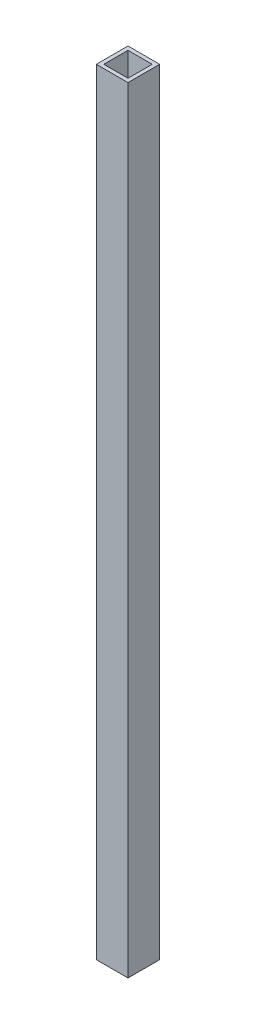
SolidWorks part; units mm, degrees
ref_plane "Front Plane" through (0, 0, 0) normal (0, 0, 1) x (1, 0, 0)
ref_plane "Top Plane" through (0, 0, 0) normal (0, 1, 0) x (1, 0, 0)
ref_plane "Right Plane" through (0, 0, 0) normal (1, 0, 0) x (0, 0, -1)
sketch "Sketch1" plane through (0, 0, 0) normal (0, 1, 0) x (1, 0, 0)
  line L1 (15.8767, 21.8352) -> (24.3767, 21.8352)
  line L2 (15.8767, 21.8352) -> (15.8767, 30.3352)
  line L3 (15.8767, 30.3352) -> (24.3767, 30.3352)
  line L4 (24.3767, 21.8352) -> (24.3767, 30.3352)
  line L5 (16.8767, 29.3352) -> (23.3767, 29.3352)
  line L6 (16.8767, 29.3352) -> (16.8767, 22.8352)
  line L7 (16.8767, 22.8352) -> (23.3767, 22.8352)
  line L8 (23.3767, 29.3352) -> (23.3767, 22.8352)
  dimension "D1" = 8.5
  dimension "D2" = 8.5
  dimension "D3" = 6.5
  dimension "D4" = 6.5
  dimension "D5" = 1
  dimension "D6" = 1
extrude "Boss-Extrude1" add sketch "Sketch1" along normal blind 208.245
